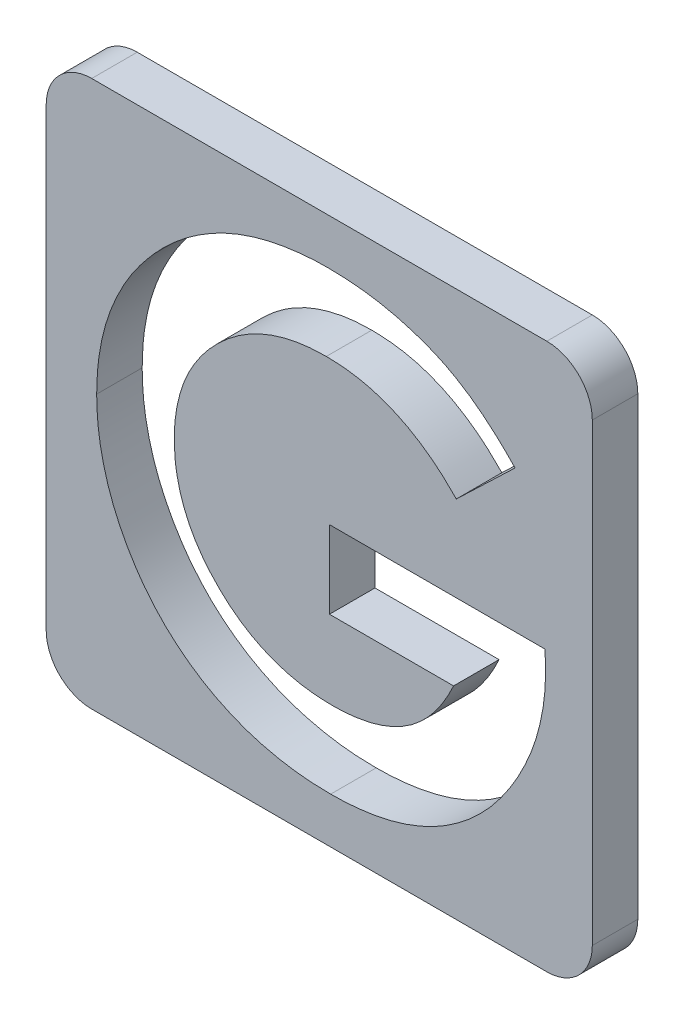
SolidWorks part; units mm, degrees
ref_plane "Front Plane" through (0, 0, 0) normal (0, 0, 1) x (1, 0, 0)
ref_plane "Top Plane" through (0, 0, 0) normal (0, 1, 0) x (1, 0, 0)
ref_plane "Right Plane" through (0, 0, 0) normal (1, 0, 0) x (0, 0, -1)
sketch "Sketch1" plane through (0, 0, 0) normal (0, 0, 1) x (1, 0, 0)
  line L1 (-50, 60) -> (50, 60)
  line L2 (-60, 50) -> (-60, -50)
  line L3 (-50, -60) -> (50, -60)
  line L4 (60, 50) -> (60, -50)
  line L5 (-60, 60) -> (60, -60) construction
  line L6 (-60, -60) -> (60, 60) construction
  arc A0 (-60, -50) -> (-50, -60) centre (-50, -50) ccw
  arc A1 (50, -60) -> (60, -50) centre (50, -50) ccw
  arc A2 (50, 60) -> (60, 50) centre (50, 50) cw
  arc A3 (-50, 60) -> (-60, 50) centre (-50, 50) ccw
  point P0 (0, 0)
  dimension "D3" = 10
  dimension "D1" = 120
  dimension "D2" = 120
extrude "Boss-Extrude1" add sketch "Sketch1" along normal blind 10 contours A3 L2 A0 L3 A1 L4 A2 L1
sketch "Sketch2" plane through (0, 0, 10) normal (0, 0, 1) x (1, 0, 0)
  line L0 (0, 0) -> (0, 40) construction
  line L1 (-50, 50) -> (50, 50) construction
  line L2 (-50, 50) -> (-50, -50) construction
  line L3 (-50, -50) -> (50, -50) construction
  line L4 (50, 50) -> (50, -50) construction
  line L5 (-50, 50) -> (50, -50) construction
  line L6 (-50, -50) -> (50, 50) construction
  line L7 (0, 40) -> (-40, 40) construction
  line L8 (-40, 40) -> (-40, 0) construction
  line L9 (-40, 0) -> (0, 0) construction
  line L11 (0, 20) -> (-20, 20) construction
  line L12 (-20, 40) -> (-20, 20) construction
  circle A0 centre (0, 40) radius 4 construction
  circle A1 centre (0, 20) radius 4 construction
  circle A2 centre (0, 0) radius 4 construction
  circle A3 centre (-20, 20) radius 4 construction
  circle A4 centre (-20, 40) radius 4 construction
  circle A5 centre (-40, 40) radius 4 construction
  circle A6 centre (0, 0) radius 4 construction
  circle A7 centre (20, 0) radius 4 construction
  circle A8 centre (40, 0) radius 4 construction
  circle A9 centre (40, 20) radius 4 construction
  circle A10 centre (40, 40) radius 4 construction
  circle A11 centre (20, 20) radius 4 construction
  circle A12 centre (0, 0) radius 4 construction
  circle A13 centre (0, -20) radius 4 construction
  circle A14 centre (0, -40) radius 4 construction
  circle A15 centre (20, -40) radius 4 construction
  circle A16 centre (40, -40) radius 4 construction
  circle A17 centre (20, -20) radius 4 construction
  circle A18 centre (0, 0) radius 4 construction
  circle A19 centre (-20, 0) radius 4 construction
  circle A20 centre (-40, 0) radius 4 construction
  circle A21 centre (-40, -20) radius 4 construction
  circle A22 centre (-40, -40) radius 4 construction
  circle A23 centre (-20, -20) radius 4 construction
  text T0 "G" font "Century Gothic" height 95
  point P0 (0, 0)
  point P55 (0, 0)
  dimension "D4" = 8
  dimension "D1" = 100
  dimension "D2" = 100
  dimension "D3" = 40
  dimension "D5" = 4
extrude "Cut-Extrude20" cut sketch "Sketch2" against normal blind 10
